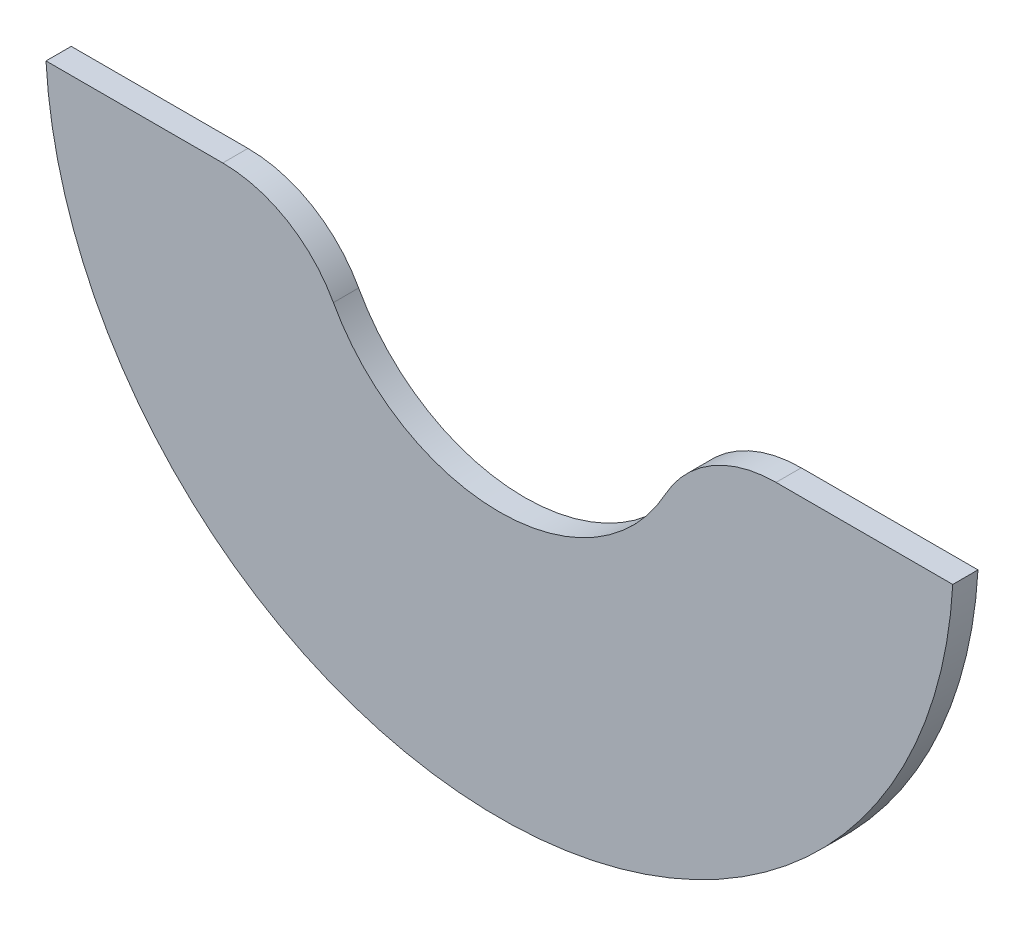
SolidWorks part; units mm, degrees
ref_plane "Front Plane" through (0, 0, 0) normal (0, 0, 1) x (1, 0, 0)
ref_plane "Top Plane" through (0, 0, 0) normal (0, 1, 0) x (1, 0, 0)
ref_plane "Right Plane" through (0, 0, 0) normal (1, 0, 0) x (0, 0, -1)
sketch "Sketch1" plane through (0, 0, 0) normal (0, 0, 1) x (1, 0, 0)
  line L0 (-17.9722, -1) -> (17.9722, -1)
  arc A0 (-17.9722, -1) -> (17.9722, -1) centre (0, 0) ccw
  dimension "D1" = 36
  dimension "D2" = 1
extrude "Boss-Extrude1" add sketch "Sketch1" along normal blind 1
sketch "Sketch2" plane through (0, 0, 1) normal (0, 0, 1) x (1, 0, 0)
  circle A1 centre (0, 0) radius 7.5
  dimension "D1" = 15
extrude "Cut-Extrude1" cut sketch "Sketch2" against normal through all
fillet "Fillet1" radius 5 2 edges at (-7.433, -1, 0.5) (7.433, -1, 0.5)
